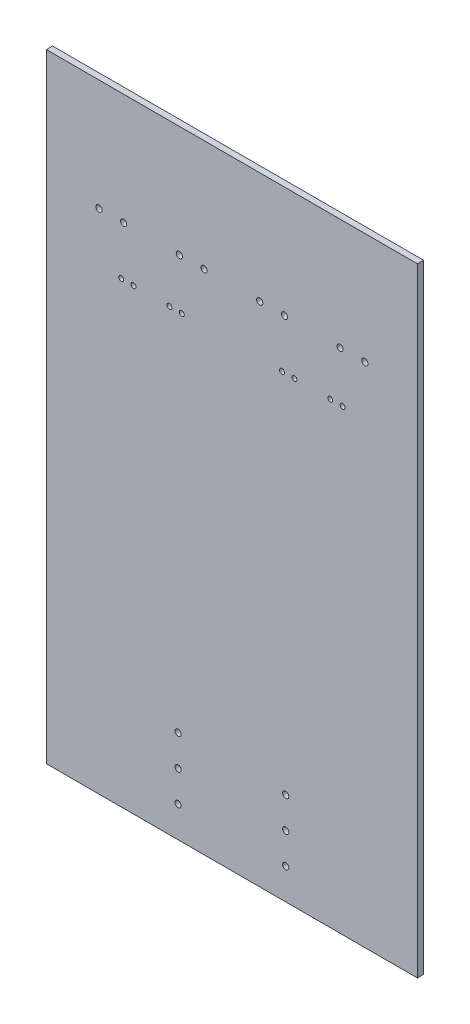
SolidWorks part; units mm, degrees
material "Oak"
ref_plane "Front Plane" through (0, 0, 0) normal (0, 0, 1) x (1, 0, 0)
ref_plane "Top Plane" through (0, 0, 0) normal (0, 1, 0) x (1, 0, 0)
ref_plane "Right Plane" through (0, 0, 0) normal (1, 0, 0) x (0, 0, -1)
sketch "Sketch1" plane through (0, 0, 0) normal (0, 0, 1) x (1, 0, 0)
  line L1 (0, 0) -> (300, 0)
  line L2 (0, 0) -> (0, 500)
  line L3 (0, 500) -> (300, 500)
  line L4 (300, 0) -> (300, 500)
  dimension "D1" = 300
  dimension "D2" = 500
extrude "Boss-Extrude1" add sketch "Sketch1" along normal blind 5
sketch "Sketch2" plane through (0, 0, 5) normal (0, 0, 1) x (1, 0, 0)
  line L0 (0, 500) -> (0, 0) construction
  line L1 (300, 0) -> (300, 500) construction
  line L2 (300, 500) -> (0, 500) construction
  circle A0 centre (42.5, 410) radius 2.5
  circle A1 centre (62.5, 410) radius 2.5
  circle A2 centre (107.5, 410) radius 2.5
  circle A3 centre (127.5, 410) radius 2.5
  circle A6 centre (172.5, 410) radius 2.5
  circle A7 centre (192.5, 410) radius 2.5
  circle A8 centre (237.5, 410) radius 2.5
  circle A13 centre (70.5, 370) radius 2
  circle A14 centre (99.5, 370) radius 2
  circle A15 centre (200.5, 370) radius 2
  circle A17 centre (257.5, 410) radius 2.5
  circle A18 centre (229.5, 370) radius 2
  circle A19 centre (60.5, 370) radius 2
  circle A20 centre (109.5, 370) radius 2
  circle A21 centre (190.5, 370) radius 2
  circle A22 centre (239.5, 370) radius 2
  dimension "D1" = 5
  dimension "D2" = 42.5
  dimension "D3" = 20
  dimension "D4" = 5
  dimension "D5" = 20
  dimension "D6" = 20
  dimension "D7" = 20
  dimension "D8" = 45
  dimension "D10" = 42.5
  dimension "D11" = 90
  dimension "D12" = 4
  dimension "D13" = 4
  dimension "D14" = 29
  dimension "D15" = 70.5
  dimension "D16" = 40
  dimension "D17" = 8
  dimension "D18" = 29
  dimension "D19" = 40
  dimension "D20" = 40
  dimension "D21" = 40
  dimension "D22" = 90
  dimension "D23" = 90
  dimension "D24" = 90
  dimension "D25" = 90
  dimension "D26" = 90
  dimension "D27" = 90
  dimension "D28" = 90
  dimension "D29" = 5
  dimension "D30" = 8
  dimension "D31" = 70.5
  dimension "D32" = 4
  dimension "D33" = 4
  dimension "D34" = 10
  dimension "D35" = 10
  dimension "D36" = 40
  dimension "D37" = 40
  dimension "D38" = 4
  dimension "D39" = 10
  dimension "D40" = 40
  dimension "D41" = 4
  dimension "D42" = 10
  dimension "D43" = 40
  dimension "D9" = 45
extrude "Cut-Extrude1" cut sketch "Sketch2" against normal blind 10
sketch "Sketch3" plane through (0, 0, 5) normal (0, 0, 1) x (1, 0, 0)
  line L0 (0, 500) -> (0, 0) construction
  line L1 (0, 0) -> (300, 0) construction
  line L2 (300, 0) -> (300, 500) construction
  circle A0 centre (106.5, 25) radius 2.5
  circle A1 centre (106.5, 50) radius 2.5
  circle A2 centre (106.5, 75) radius 2.5
  circle A3 centre (193.5, 25) radius 2.5
  circle A4 centre (193.5, 50) radius 2.5
  circle A5 centre (193.5, 75) radius 2.5
  dimension "D1" = 106.5
  dimension "D2" = 25
  dimension "D3" = 5
  dimension "D4" = 5
  dimension "D5" = 5
  dimension "D6" = 25
  dimension "D7" = 25
  dimension "D8" = 106.5
  dimension "D10" = 5
  dimension "D11" = 5
  dimension "D12" = 5
  dimension "D13" = 106.5
  dimension "D14" = 106.5
  dimension "D15" = 106.5
  dimension "D16" = 25
  dimension "D17" = 25
  dimension "D18" = 25
  dimension "D9" = 106.5
extrude "Cut-Extrude2" cut sketch "Sketch3" against normal blind 10
